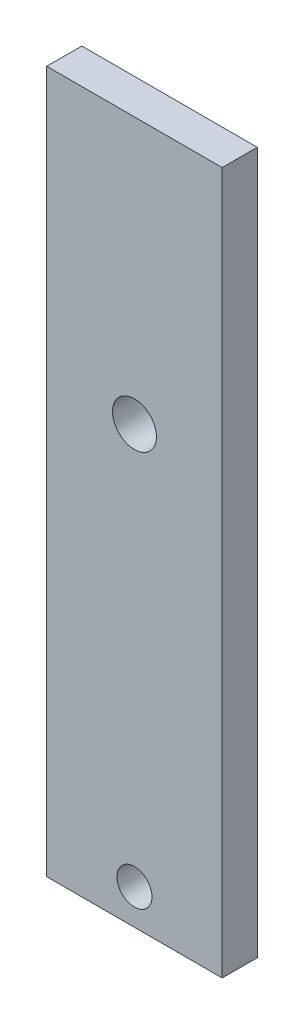
SolidWorks part; units mm, degrees
ref_plane "Front Plane" through (0, 0, 0) normal (0, 0, 1) x (1, 0, 0)
ref_plane "Top Plane" through (0, 0, 0) normal (0, 1, 0) x (1, 0, 0)
ref_plane "Right Plane" through (0, 0, 0) normal (1, 0, 0) x (0, 0, -1)
sketch "Sketch1" plane through (0, 0, 0) normal (0, 0, 1) x (1, 0, 0)
  line L1 (-5, -25) -> (5, -25)
  line L2 (-5, -25) -> (-5, 15)
  line L3 (-5, 15) -> (5, 15)
  line L4 (5, -25) -> (5, 15)
  point P0 (0, 0)
  dimension "D1" = 10
  dimension "D2" = 15
  dimension "D3" = 25
extrude "Boss-Extrude1" add sketch "Sketch1" along normal blind 2
hole_wizard "M3x0.5 Tapped Hole1" positions "Sketch2" profile "Sketch4" tap size "M3x0.5" standard "ANSI Metric" end condition through all
sketch "Sketch2" plane through (0, 0, 2) normal (0, 0, 1) x (1, 0, 0)
  point P0 (0, -0.1649)
sketch "Sketch4" plane through (0, -0.1649, 2) normal (1, 0, 0) x (0, -1, 0)
  line L0 (0, 0) -> (0, 2)
  line L1 (0, 2) -> (1.25, 2)
  line L2 (1.25, 2) -> (1.25, 0)
  line L5 (1.25, 0) -> (0, 0)
  line L11 (0, -6.35) -> (0, 107.95) construction
  dimension "Thru Tap Drill Dia." = 2.5
  dimension "Thru Tap Drill Depth" = 2
cosmetic thread "Hole Thread1"
sketch "Sketch6" plane through (0, 0, 2) normal (0, 0, 1) x (1, 0, 0)
  line L0 (0, 0.2028) -> (0, -15.3336) construction
  line L1 (-5, -25) -> (5, -25) construction
  circle A0 centre (0, -23) radius 1
  dimension "D2" = 2
  dimension "D1" = 2
extrude "Cut-Extrude1" cut sketch "Sketch6" against normal up to next
